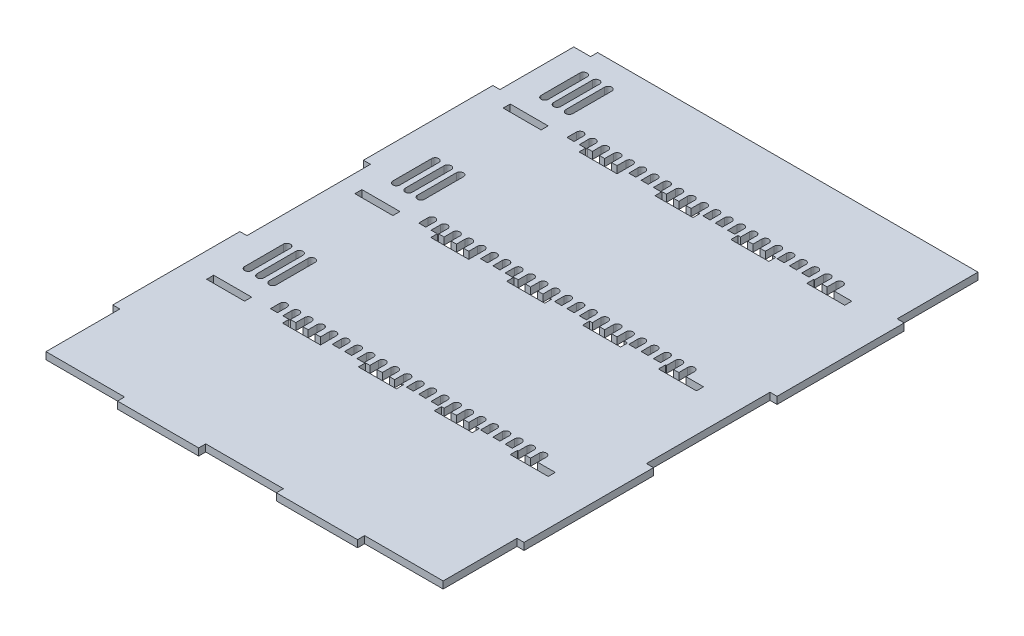
SolidWorks part; units mm, degrees
ref_plane "Front Plane" through (0, 0, 0) normal (0, 0, 1) x (1, 0, 0)
ref_plane "Top Plane" through (0, 0, 0) normal (0, 1, 0) x (1, 0, 0)
ref_plane "Right Plane" through (0, 0, 0) normal (1, 0, 0) x (0, 0, -1)
sketch "Sketch1" plane through (0, 0, 0) normal (0, 1, 0) x (1, 0, 0)
  line L1 (0, 0) -> (233, 0)
  line L2 (0, 0) -> (0, 307)
  line L3 (0, 307) -> (233, 307)
  line L4 (233, 0) -> (233, 307)
  dimension "D1" = 233
  dimension "D2" = 307
extrude "Boss-Extrude1" add sketch "Sketch1" along normal blind 4
sketch "Sketch2" plane through (0, 4, 0) normal (0, 1, 0) x (1, 0, 0)
  line L1 (0, 307) -> (4, 307)
  line L2 (0, 307) -> (0, 261.1667)
  line L3 (0, 261.1667) -> (4, 261.1667)
  line L4 (4, 307) -> (4, 261.1667)
  line L5 (0, 0) -> (4, 0)
  line L6 (0, 0) -> (0, 45.8333)
  line L7 (0, 45.8333) -> (4, 45.8333)
  line L8 (4, 0) -> (4, 45.8333)
  line L9 (233, 0) -> (233, 307) construction
  line L10 (0, 0) -> (233, 0) construction
  line L11 (4, 307) -> (13.5, 307)
  line L12 (4, 307) -> (4, 303)
  line L13 (4, 303) -> (13.5, 303)
  line L14 (13.5, 307) -> (13.5, 303)
  line L15 (94.5, 0) -> (94.5, 4)
  line L16 (4, 0) -> (48.5, 0)
  line L17 (4, 0) -> (4, 4)
  line L18 (4, 4) -> (48.5, 4)
  line L19 (48.5, 0) -> (48.5, 4)
  line L20 (94.5, 0) -> (138.5, 0)
  line L21 (138.5, 0) -> (138.5, 4)
  line L22 (94.5, 4) -> (138.5, 4)
  line L23 (184.5, 0) -> (184.5, 4)
  line L24 (184.5, 0) -> (229, 0)
  line L26 (184.5, 4) -> (229, 4)
  line L27 (229, 307) -> (229, 261.1667)
  line L28 (229, 307) -> (233, 307)
  line L29 (233, 307) -> (233, 261.1667)
  line L30 (229, 261.1667) -> (233, 261.1667)
  line L31 (229, 0) -> (229, 45.8333)
  line L32 (229, 0) -> (233, 0)
  line L33 (233, 0) -> (233, 45.8333)
  line L34 (229, 45.8333) -> (233, 45.8333)
  dimension "D1" = 45.8333
  dimension "D2" = 45.8333
  dimension "D3" = 4
  dimension "D4" = 9.5
  dimension "D5" = 4
  dimension "D6" = 44.5
  dimension "D7" = 4
  dimension "D10" = 46
  dimension "D8" = 44
  dimension "D11" = 46
  dimension "D9" = 2
extrude "Cut-Extrude1" cut sketch "Sketch2" against normal blind 4
sketch "Sketch3" plane through (0, 0, 0) normal (0, -1, 0) x (1, 0, 0)
  line L7 (207.5, -253) -> (186, -253)
  line L8 (207.5, -253) -> (207.5, -257)
  line L9 (207.5, -257) -> (186, -257)
  line L10 (186, -253) -> (186, -257)
  line L12 (164.5, -253) -> (164.5, -257)
  line L13 (164.5, -253) -> (143, -253)
  line L14 (143, -253) -> (143, -257)
  line L15 (164.5, -257) -> (143, -257)
  line L16 (121.5, -253) -> (121.5, -257)
  line L17 (121.5, -253) -> (100, -253)
  line L18 (100, -253) -> (100, -257)
  line L19 (121.5, -257) -> (100, -257)
  line L20 (78.5, -253) -> (78.5, -257)
  line L21 (78.5, -253) -> (57, -253)
  line L22 (57, -253) -> (57, -257)
  line L23 (78.5, -257) -> (57, -257)
  line L24 (35.5, -253) -> (35.5, -257)
  line L25 (35.5, -253) -> (14, -253)
  line L26 (14, -253) -> (14, -257)
  line L27 (35.5, -257) -> (14, -257)
  line L106 (229, -307) -> (13.5, -307) construction
  line L107 (35.5, -169) -> (35.5, -173)
  line L108 (35.5, -173) -> (14, -173)
  line L109 (14, -169) -> (14, -173)
  line L110 (35.5, -169) -> (14, -169)
  line L111 (78.5, -169) -> (78.5, -173)
  line L112 (78.5, -173) -> (57, -173)
  line L113 (57, -169) -> (57, -173)
  line L114 (78.5, -169) -> (57, -169)
  line L115 (121.5, -169) -> (121.5, -173)
  line L116 (121.5, -173) -> (100, -173)
  line L117 (100, -169) -> (100, -173)
  line L118 (121.5, -169) -> (100, -169)
  line L119 (164.5, -169) -> (164.5, -173)
  line L120 (164.5, -173) -> (143, -173)
  line L121 (143, -169) -> (143, -173)
  line L122 (164.5, -169) -> (143, -169)
  line L123 (207.5, -169) -> (207.5, -173)
  line L124 (207.5, -169) -> (186, -169)
  line L125 (186, -169) -> (186, -173)
  line L126 (207.5, -173) -> (186, -173)
  line L127 (35.5, -85) -> (35.5, -89)
  line L128 (35.5, -89) -> (14, -89)
  line L129 (14, -85) -> (14, -89)
  line L130 (35.5, -85) -> (14, -85)
  line L131 (78.5, -85) -> (78.5, -89)
  line L132 (78.5, -89) -> (57, -89)
  line L133 (57, -85) -> (57, -89)
  line L134 (78.5, -85) -> (57, -85)
  line L135 (121.5, -85) -> (121.5, -89)
  line L136 (121.5, -89) -> (100, -89)
  line L137 (100, -85) -> (100, -89)
  line L138 (121.5, -85) -> (100, -85)
  line L139 (164.5, -85) -> (164.5, -89)
  line L140 (164.5, -89) -> (143, -89)
  line L141 (143, -85) -> (143, -89)
  line L142 (164.5, -85) -> (143, -85)
  line L143 (207.5, -85) -> (207.5, -89)
  line L144 (207.5, -85) -> (186, -85)
  line L145 (186, -85) -> (186, -89)
  line L146 (207.5, -89) -> (186, -89)
  dimension "D1" = 50
  dimension "D2" = 21.5
  dimension "D3" = 4
  dimension "D5" = 5
extrude "Cut-Extrude2" cut sketch "Sketch3" against normal blind 4
sketch "Sketch4" plane through (0, 4, 0) normal (0, 1, 0) x (1, 0, 0)
  line L0 (0, 261.1667) -> (0, 45.8333) construction
  line L1 (0, 187.8333) -> (4, 187.8333)
  line L2 (0, 187.8333) -> (0, 117.8333)
  line L3 (0, 117.8333) -> (4, 117.8333)
  line L4 (4, 187.8333) -> (4, 117.8333)
  line L5 (0, 45.8333) -> (4, 45.8333) construction
  point P6 (4, 152.8333)
  dimension "D1" = 4
  dimension "D2" = 70
  dimension "D3" = 107
extrude "Cut-Extrude3" cut sketch "Sketch4" against normal blind 4
sketch "Sketch5" plane through (0, 4, 0) normal (0, 1, 0) x (1, 0, 0)
  line L0 (233, 45.8333) -> (233, 261.1667) construction
  line L1 (233, 189.1667) -> (229, 189.1667)
  line L2 (233, 189.1667) -> (233, 119.1667)
  line L3 (233, 119.1667) -> (229, 119.1667)
  line L4 (229, 189.1667) -> (229, 119.1667)
  line L5 (229, 261.1667) -> (233, 261.1667) construction
  point P6 (233, 154.1667)
  dimension "D1" = 4
  dimension "D2" = 70
  dimension "D3" = 107
extrude "Cut-Extrude4" cut sketch "Sketch5" against normal blind 4
sketch "Sketch6" plane through (0, 4, 0) normal (0, 1, 0) x (1, 0, 0)
  line L0 (20.5, 292) -> (20.5, 270) construction
  line L1 (22.5, 292) -> (22.5, 270)
  line L2 (18.5, 292) -> (18.5, 270)
  line L4 (4, 303) -> (13.5, 303) construction
  line L11 (13.5, 307) -> (13.5, 303) construction
  line L17 (109.5011, 256.6579) -> (113.5011, 256.6579)
  line L18 (25.5402, 292) -> (25.5402, 270)
  line L21 (29.5402, 292) -> (29.5402, 270)
  line L22 (27.5402, 292) -> (27.5402, 270) construction
  line L23 (34.4609, 292) -> (34.4609, 270) construction
  line L24 (36.4609, 292) -> (36.4609, 270)
  line L25 (32.4609, 292) -> (32.4609, 270)
  line L26 (102.5011, 261.9985) -> (102.5011, 256.6579)
  line L27 (111.5011, 261.9985) -> (111.5011, 258.9985) construction
  line L29 (113.5011, 261.9985) -> (113.5011, 256.6579)
  line L30 (109.5011, 261.9985) -> (109.5011, 256.6579)
  line L31 (102.5011, 256.6579) -> (106.5011, 256.6579)
  line L32 (106.5011, 261.9985) -> (106.5011, 256.6579)
  line L33 (95.5011, 261.9985) -> (95.5011, 256.6579)
  line L34 (95.5011, 256.6579) -> (99.5011, 256.6579)
  line L35 (99.5011, 261.9985) -> (99.5011, 256.6579)
  line L36 (88.5011, 261.9985) -> (88.5011, 256.6579)
  line L37 (88.5011, 256.6579) -> (92.5011, 256.6579)
  line L38 (92.5011, 261.9985) -> (92.5011, 256.6579)
  line L39 (81.5011, 261.9985) -> (81.5011, 256.6579)
  line L40 (81.5011, 256.6579) -> (85.5011, 256.6579)
  line L41 (85.5011, 261.9985) -> (85.5011, 256.6579)
  line L42 (74.5011, 261.9985) -> (74.5011, 256.6579)
  line L43 (74.5011, 256.6579) -> (78.5011, 256.6579)
  line L44 (78.5011, 261.9985) -> (78.5011, 256.6579)
  line L45 (67.5011, 261.9985) -> (67.5011, 256.6579)
  line L46 (67.5011, 256.6579) -> (71.5011, 256.6579)
  line L47 (71.5011, 261.9985) -> (71.5011, 256.6579)
  line L48 (60.5011, 261.9985) -> (60.5011, 256.6579)
  line L49 (60.5011, 256.6579) -> (64.5011, 256.6579)
  line L50 (64.5011, 261.9985) -> (64.5011, 256.6579)
  line L51 (53.5011, 261.9985) -> (53.5011, 256.6579)
  line L52 (53.5011, 256.6579) -> (57.5011, 256.6579)
  line L53 (57.5011, 261.9985) -> (57.5011, 256.6579)
  line L54 (116.5011, 261.9985) -> (116.5011, 256.6579)
  line L55 (116.5011, 256.6579) -> (120.5011, 256.6579)
  line L56 (120.5011, 261.9985) -> (120.5011, 256.6579)
  line L57 (123.5011, 261.9985) -> (123.5011, 256.6579)
  line L58 (123.5011, 256.6579) -> (127.5011, 256.6579)
  line L59 (127.5011, 261.9985) -> (127.5011, 256.6579)
  line L60 (130.5011, 261.9985) -> (130.5011, 256.6579)
  line L61 (130.5011, 256.6579) -> (134.5011, 256.6579)
  line L62 (134.5011, 261.9985) -> (134.5011, 256.6579)
  line L63 (137.5011, 261.9985) -> (137.5011, 256.6579)
  line L64 (137.5011, 256.6579) -> (141.5011, 256.6579)
  line L65 (141.5011, 261.9985) -> (141.5011, 256.6579)
  line L66 (144.5011, 261.9985) -> (144.5011, 256.6579)
  line L67 (144.5011, 256.6579) -> (148.5011, 256.6579)
  line L68 (148.5011, 261.9985) -> (148.5011, 256.6579)
  line L69 (151.5011, 261.9985) -> (151.5011, 256.6579)
  line L70 (151.5011, 256.6579) -> (155.5011, 256.6579)
  line L71 (155.5011, 261.9985) -> (155.5011, 256.6579)
  line L72 (158.5011, 261.9985) -> (158.5011, 256.6579)
  line L73 (158.5011, 256.6579) -> (162.5011, 256.6579)
  line L74 (162.5011, 261.9985) -> (162.5011, 256.6579)
  line L75 (165.5011, 261.9985) -> (165.5011, 256.6579)
  line L76 (165.5011, 256.6579) -> (169.5011, 256.6579)
  line L77 (169.5011, 261.9985) -> (169.5011, 256.6579)
  line L78 (172.5011, 261.9985) -> (172.5011, 256.6579)
  line L79 (172.5011, 256.6579) -> (176.5011, 256.6579)
  line L80 (176.5011, 261.9985) -> (176.5011, 256.6579)
  line L81 (179.5011, 261.9985) -> (179.5011, 256.6579)
  line L82 (179.5011, 256.6579) -> (183.5011, 256.6579)
  line L83 (183.5011, 261.9985) -> (183.5011, 256.6579)
  line L84 (186.5011, 261.9985) -> (186.5011, 256.6579)
  line L85 (186.5011, 256.6579) -> (190.5011, 256.6579)
  line L86 (190.5011, 261.9985) -> (190.5011, 256.6579)
  line L87 (46.5011, 261.9985) -> (46.5011, 256.6579)
  line L88 (46.5011, 256.6579) -> (50.5011, 256.6579)
  line L89 (50.5011, 261.9985) -> (50.5011, 256.6579)
  line L90 (193.5011, 261.9985) -> (193.5011, 256.6579)
  line L91 (193.5011, 256.6579) -> (197.5011, 256.6579)
  line L92 (197.5011, 261.9985) -> (197.5011, 256.6579)
  arc A0 (22.5, 292) -> (18.5, 292) centre (20.5, 292) ccw
  arc A1 (18.5, 270) -> (22.5, 270) centre (20.5, 270) ccw
  arc A14 (29.5402, 292) -> (25.5402, 292) centre (27.5402, 292) ccw
  arc A15 (25.5402, 270) -> (29.5402, 270) centre (27.5402, 270) ccw
  arc A16 (36.4609, 292) -> (32.4609, 292) centre (34.4609, 292) ccw
  arc A17 (32.4609, 270) -> (36.4609, 270) centre (34.4609, 270) ccw
  arc A18 (113.5011, 261.9985) -> (109.5011, 261.9985) centre (111.5011, 261.9985) ccw
  arc A20 (106.5011, 261.9985) -> (102.5011, 261.9985) centre (104.5011, 261.9985) ccw
  arc A21 (99.5011, 261.9985) -> (95.5011, 261.9985) centre (97.5011, 261.9985) ccw
  arc A22 (92.5011, 261.9985) -> (88.5011, 261.9985) centre (90.5011, 261.9985) ccw
  arc A23 (85.5011, 261.9985) -> (81.5011, 261.9985) centre (83.5011, 261.9985) ccw
  arc A24 (78.5011, 261.9985) -> (74.5011, 261.9985) centre (76.5011, 261.9985) ccw
  arc A25 (71.5011, 261.9985) -> (67.5011, 261.9985) centre (69.5011, 261.9985) ccw
  arc A26 (64.5011, 261.9985) -> (60.5011, 261.9985) centre (62.5011, 261.9985) ccw
  arc A27 (57.5011, 261.9985) -> (53.5011, 261.9985) centre (55.5011, 261.9985) ccw
  arc A28 (120.5011, 261.9985) -> (116.5011, 261.9985) centre (118.5011, 261.9985) ccw
  arc A29 (127.5011, 261.9985) -> (123.5011, 261.9985) centre (125.5011, 261.9985) ccw
  arc A30 (134.5011, 261.9985) -> (130.5011, 261.9985) centre (132.5011, 261.9985) ccw
  arc A31 (141.5011, 261.9985) -> (137.5011, 261.9985) centre (139.5011, 261.9985) ccw
  arc A32 (148.5011, 261.9985) -> (144.5011, 261.9985) centre (146.5011, 261.9985) ccw
  arc A33 (155.5011, 261.9985) -> (151.5011, 261.9985) centre (153.5011, 261.9985) ccw
  arc A34 (162.5011, 261.9985) -> (158.5011, 261.9985) centre (160.5011, 261.9985) ccw
  arc A35 (169.5011, 261.9985) -> (165.5011, 261.9985) centre (167.5011, 261.9985) ccw
  arc A36 (176.5011, 261.9985) -> (172.5011, 261.9985) centre (174.5011, 261.9985) ccw
  arc A37 (183.5011, 261.9985) -> (179.5011, 261.9985) centre (181.5011, 261.9985) ccw
  arc A38 (190.5011, 261.9985) -> (186.5011, 261.9985) centre (188.5011, 261.9985) ccw
  arc A39 (50.5011, 261.9985) -> (46.5011, 261.9985) centre (48.5011, 261.9985) ccw
  arc A40 (197.5011, 261.9985) -> (193.5011, 261.9985) centre (195.5011, 261.9985) ccw
  point P2 (20.5, 281)
  point P14 (111.5011, 260.4985)
  point P16 (27.5402, 281)
  point P23 (34.4609, 281)
  dimension "D2" = 4
  dimension "D3" = 2
  dimension "D4" = 2
  dimension "D6" = 2
  dimension "D8" = 4
  dimension "D10" = 7
  dimension "D11" = 8.0015
  dimension "D7" = 22
  dimension "D9" = 11
  dimension "D5" = 2
  dimension "D13" = 9
  dimension "D14" = 12
extrude "Cut-Extrude5" cut sketch "Sketch6" against normal blind 4
pattern_linear "LPattern1" count 3 spacing 84 along (0, 0, 1) of "Cut-Extrude5"
equation "\"Dikte\"= 4"
equation "\"D1@Sketch1\"=\"Dikte\"*2+225"
equation "\"D2@Sketch1\"=135+\"Dikte\" + 34*2 + 50*2"
equation "\"D1@Sketch2\"=139/3-\"Tolerantie\""
equation "\"D2@Sketch2\"=\"D1@Sketch2\""
equation "\"D5@Sketch2\"=\"Dikte\""
equation "\"Tolerantie\"= 0.5"
equation "\"D6@Sketch2\"=45-\"Tolerantie\""
equation "\"D10@Sketch2\"=45+2*\"Tolerantie\""
equation "\"D8@Sketch2\"=45-2*\"Tolerantie\""
equation "\"D11@Sketch2\"=\"D10@Sketch2\""
equation "\"D4@Sketch2\"=10-\"Tolerantie\""
